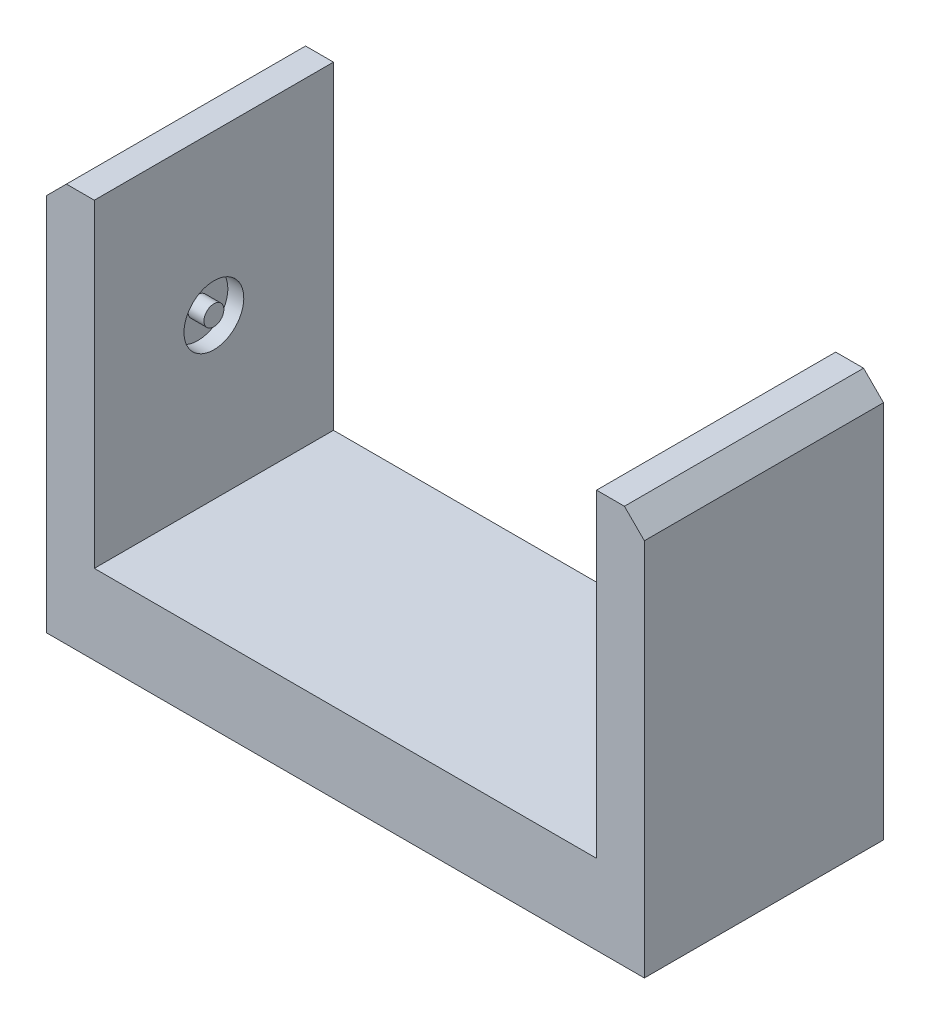
SolidWorks part; units mm, degrees
ref_plane "前视基准面" through (0, 0, 0) normal (0, 0, 1) x (1, 0, 0)
ref_plane "上视基准面" through (0, 0, 0) normal (0, 1, 0) x (1, 0, 0)
ref_plane "右视基准面" through (0, 0, 0) normal (1, 0, 0) x (0, 0, -1)
sketch "草图1" plane through (0, 0, 0) normal (0, 0, 1) x (1, 0, 0)
  line L0 (-70, 100) -> (-63, 100)
  line L1 (-75, 0) -> (75, 0)
  line L2 (-75, 0) -> (-75, 95)
  line L3 (-63, 100) -> (-63, 20)
  line L4 (-75, 95) -> (-70, 100)
  line L5 (75, 95) -> (70, 100)
  line L6 (63, 100) -> (63, 20)
  line L7 (-63, 20) -> (63, 20)
  line L8 (70, 100) -> (63, 100)
  line L10 (0, 20) -> (0, 0)
  line L13 (75, 0) -> (75, 95)
  point P0 (0, 0)
  point P3 (-75, 100)
  point P16 (75, 100)
  dimension "D1" = 75
  dimension "D2" = 100
  dimension "D3" = 20
  dimension "D4" = 12
extrude "凸台-拉伸1" add sketch "草图1" along normal mid plane 60 contours L10 L7 L3 L0 L4 L2 L1 | L1 L13 L5 L8 L6 L7 L10
sketch "草图2" plane through (0, 0, 0) normal (0, -1, 0) x (1, 0, 0)
  circle A0 centre (0, 0) radius 20
  circle A1 centre (0, 0) radius 18
  dimension "D1" = 40
  dimension "D2" = 36
extrude "凸台-拉伸2" add sketch "草图2" along normal blind 10
sketch "草图3" plane through (-63, 0, 0) normal (1, 0, 0) x (0, 0, -1)
  line L5 (-30, 100) -> (30, 100) construction
  circle A0 centre (0, 60) radius 7.5
  circle A1 centre (0, 60) radius 2.5
  dimension "D1" = 15
  dimension "D3" = 5
  dimension "D2" = 40
extrude "切除-拉伸1" cut sketch "草图3" against normal blind 4 contours A0 A1
mirror "镜向1" about plane through (0, 0, 0) normal (1, 0, 0) of "切除-拉伸1"
